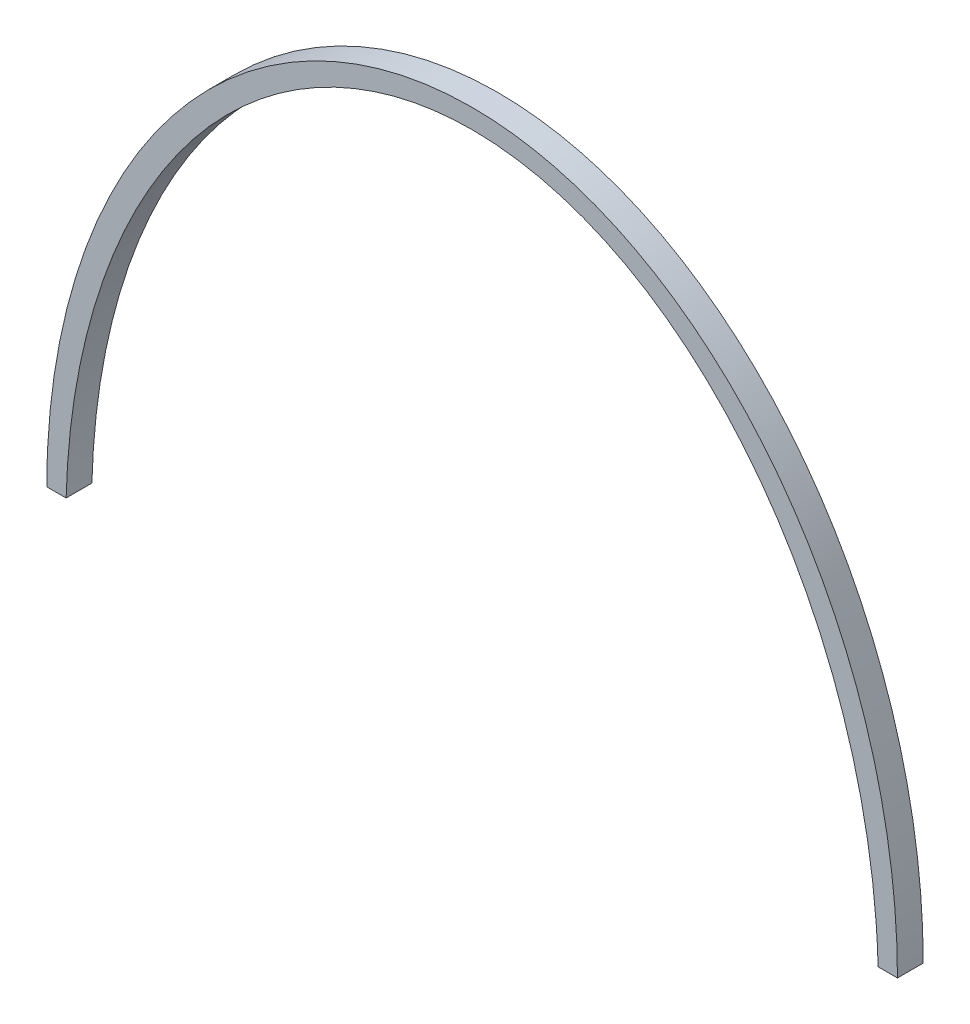
SolidWorks part; units mm, degrees
ref_plane "Front Plane" through (0, 0, 0) normal (0, 0, 1) x (1, 0, 0)
ref_plane "Top Plane" through (0, 0, 0) normal (0, 1, 0) x (1, 0, 0)
ref_plane "Right Plane" through (0, 0, 0) normal (1, 0, 0) x (0, 0, -1)
sketch "Sketch1" plane through (0, 0, 0) normal (0, 0, 1) x (1, 0, 0)
  line L5 (400.05, 0) -> (419.1, 0) construction
  line L6 (-419.1, 0) -> (-400.05, 0) construction
  line L7 (400.05, 0) -> (419.1, 0)
  line L8 (-419.1, 0) -> (-400.05, 0)
  ellipse E0 centre (0, 0) end of major axis (0, -533.4) minor radius 419.1 (419.1, 0) -> (-419.1, 0) ccw construction
  ellipse E1 centre (0, -19.05) end of major axis (0, -552.45) minor radius 400.3054 (400.05, 0) -> (-400.05, 0) ccw construction
  ellipse E2 centre (0, 0) end of major axis (0, -533.4) minor radius 419.1 (419.1, 0) -> (-419.1, 0) ccw
  ellipse E3 centre (0, -19.05) end of major axis (0, -552.45) minor radius 400.3054 (400.05, 0) -> (-400.05, 0) ccw
extrude "Boss-Extrude1" add sketch "Sketch1" along normal mid plane 25.4
